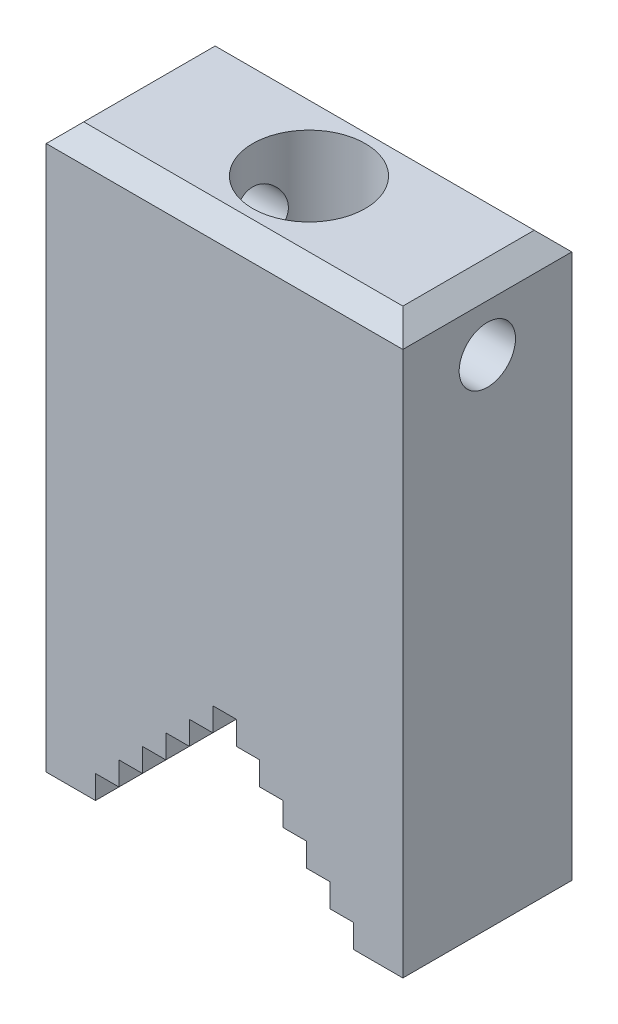
SolidWorks part; units mm, degrees
ref_plane "Front Plane" through (0, 0, 0) normal (0, 0, 1) x (1, 0, 0)
ref_plane "Top Plane" through (0, 0, 0) normal (0, 1, 0) x (1, 0, 0)
ref_plane "Right Plane" through (0, 0, 0) normal (1, 0, 0) x (0, 0, -1)
sketch "Sketch1" plane through (0, 0, 0) normal (1, 0, 0) x (0, 0, -1)
  line L1 (9, -30) -> (-9, -30)
  line L2 (9, -30) -> (9, 30)
  line L3 (9, 30) -> (-9, 30)
  line L4 (-9, -30) -> (-9, 30)
  line L5 (9, -30) -> (-9, 30) construction
  line L6 (9, 30) -> (-9, -30) construction
  circle A0 centre (0, 23) radius 3
  point P0 (0, 0)
  point P9 (0, 30)
  dimension "D3" = 6
  dimension "D1" = 18
  dimension "D2" = 60
  dimension "D4" = 7
extrude "Boss-Extrude1" add sketch "Sketch1" against normal blind 38
chamfer "Chamfer1" distance 2 angle 45 4 edges at (0, 30, 0) (-19, 30, -9) (-38, 30, 0) (-19, 30, 9)
sketch "Sketch2" plane through (0, 0, 9) normal (0, 0, 1) x (1, 0, 0)
  line L0 (-19, -30) -> (-19, 40.9077) construction
  line L1 (-38, -30) -> (0, -30) construction
  line L2 (-32.75, -30) -> (-32.75, -27.5)
  line L3 (-32.75, -27.5) -> (-30.25, -27.5)
  line L4 (-30.25, -27.5) -> (-30.25, -25)
  line L5 (-30.25, -25) -> (-27.75, -25)
  line L6 (-27.75, -25) -> (-27.75, -22.5)
  line L7 (-27.75, -22.5) -> (-25.25, -22.5)
  line L8 (-25.25, -22.5) -> (-25.25, -20)
  line L9 (-25.25, -20) -> (-22.75, -20)
  line L10 (-22.75, -20) -> (-22.75, -17.5)
  line L11 (-22.75, -17.5) -> (-20.25, -17.5)
  line L12 (-20.25, -17.5) -> (-20.25, -15)
  line L13 (-17.75, -17.5) -> (-17.75, -15)
  line L14 (-15.25, -17.5) -> (-17.75, -17.5)
  line L15 (-15.25, -20) -> (-15.25, -17.5)
  line L16 (-12.75, -20) -> (-15.25, -20)
  line L17 (-12.75, -22.5) -> (-12.75, -20)
  line L18 (-10.25, -22.5) -> (-12.75, -22.5)
  line L19 (-10.25, -25) -> (-10.25, -22.5)
  line L20 (-7.75, -25) -> (-10.25, -25)
  line L21 (-7.75, -27.5) -> (-7.75, -25)
  line L22 (-5.25, -27.5) -> (-7.75, -27.5)
  line L23 (-5.25, -30) -> (-5.25, -27.5)
  line L24 (-17.75, -15) -> (-20.25, -15)
  line L25 (-32.75, -30) -> (-5.25, -30)
  dimension "D1" = 2.5
extrude "Cut-Extrude1" cut sketch "Sketch2" against normal blind 38
hole_wizard "M12x1.25 Tapped Hole1" positions "Sketch3" profile "Sketch5" tap size "M12x1.25" standard "ANSI Metric"
sketch "Sketch3" plane through (0, 30, 0) normal (0, 1, 0) x (1, 0, 0)
  point P0 (-19, 0)
  dimension "D1" = 19
sketch "Sketch5" plane through (-19, 30, 0) normal (1, 0, 0) x (0, 0, 1)
  line L0 (0, 0) -> (0, 23.4641)
  line L1 (0, 23.4641) -> (6, 20)
  line L2 (6, 20) -> (6, 0)
  line L5 (6, 0) -> (0, 0)
  line L10 (0, 23.4641) -> (-6, 20) construction
  line L11 (0, -6.35) -> (0, 107.95) construction
  dimension "Tap Drill Dia." = 12
  dimension "Tap Drill Depth" = 20
  dimension "Drill Angle" = 120
